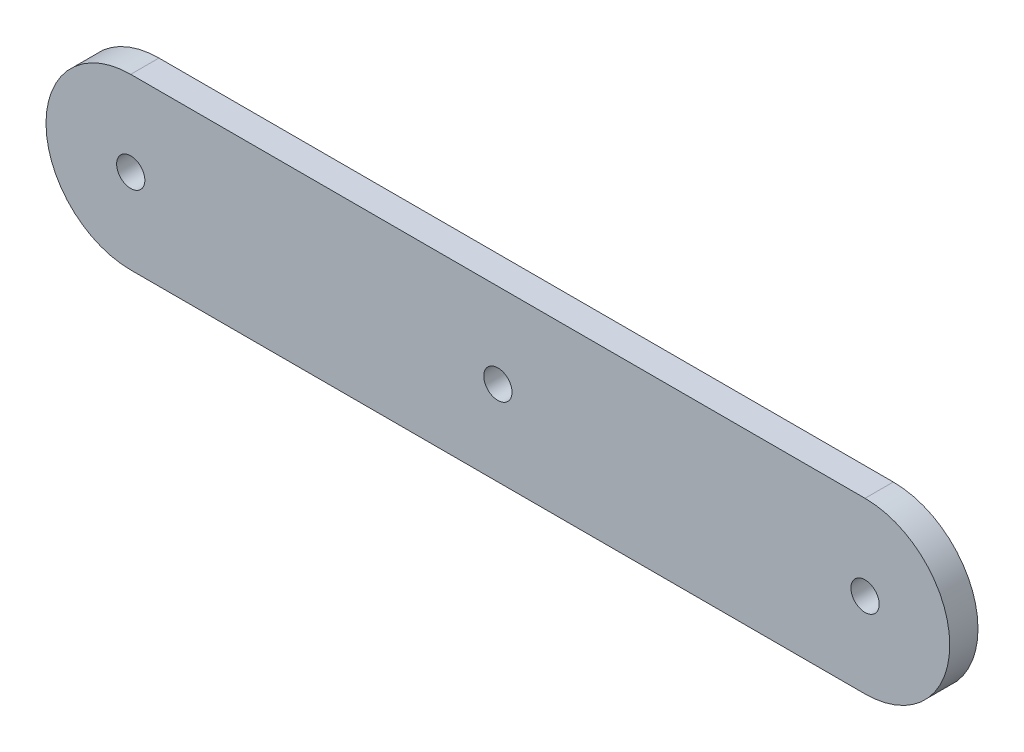
SolidWorks part; units mm, degrees
ref_plane "Front Plane" through (0, 0, 0) normal (0, 0, 1) x (1, 0, 0)
ref_plane "Top Plane" through (0, 0, 0) normal (0, 1, 0) x (1, 0, 0)
ref_plane "Right Plane" through (0, 0, 0) normal (1, 0, 0) x (0, 0, -1)
sketch "Sketch1" plane through (0, 0, 0) normal (0, 0, 1) x (1, 0, 0)
  line L0 (-67.0248, 22.2853) -> (62.9752, 22.2853) construction
  line L1 (-67.0248, 37.2853) -> (62.9752, 37.2853)
  line L2 (-67.0248, 7.2853) -> (62.9752, 7.2853)
  arc A0 (-67.0248, 37.2853) -> (-67.0248, 7.2853) centre (-67.0248, 22.2853) ccw
  arc A1 (62.9752, 7.2853) -> (62.9752, 37.2853) centre (62.9752, 22.2853) ccw
  circle A2 centre (-67.0248, 22.2853) radius 2.5
  circle A3 centre (62.9752, 22.2853) radius 2.5
  point P2 (-2.0248, 22.2853)
  dimension "D3" = 5
  dimension "D4" = 5
  dimension "D1" = 130
  dimension "D2" = 30
extrude "Boss-Extrude1" add sketch "Sketch1" along normal blind 5
sketch "Sketch2" plane through (0, 0, 0) normal (0, 0, -1) x (-1, 0, 0)
  line L0 (-62.9752, 22.2853) -> (67.0248, 22.2853)
  circle A0 centre (2.0248, 22.2853) radius 2.5
  dimension "D1" = 5
extrude "Cut-Extrude1" cut sketch "Sketch2" against normal blind 5 contours A0
